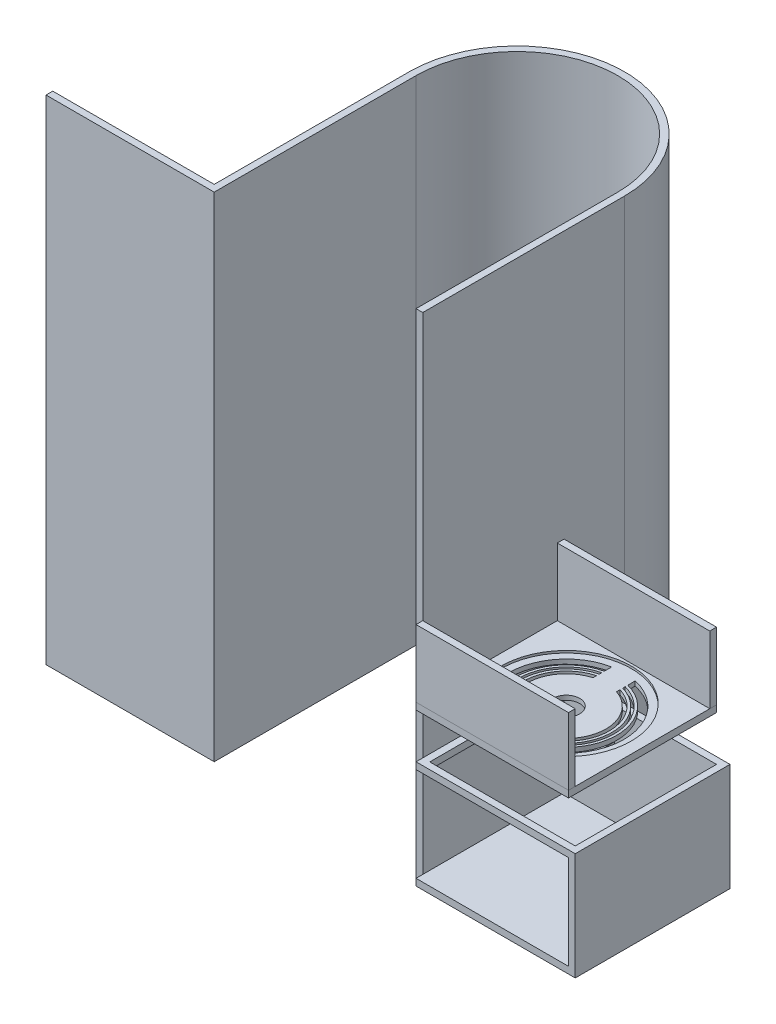
SolidWorks part; units mm, degrees
ref_plane "前视基准面" through (0, 0, 0) normal (0, 0, 1) x (1, 0, 0)
ref_plane "上视基准面" through (0, 0, 0) normal (0, 1, 0) x (1, 0, 0)
ref_plane "右视基准面" through (0, 0, 0) normal (1, 0, 0) x (0, 0, -1)
sketch "草图1" plane through (0, 0, 0) normal (0, 1, 0) x (1, 0, 0)
  line L0 (0, 0) -> (75, 0)
  line L1 (75, 0) -> (75, 90)
  line L3 (165, 0) -> (165, 90)
  arc A0 (75, 90) -> (165, 90) centre (120, 90) cw
extrude "拉伸-薄壁1" add sketch "草图1" along normal blind 220 thin thin type one direction wall 3
sketch "草图2" plane through (0, 0, 0) normal (0, 0, 1) x (1, 0, 0)
  line L0 (168, 220) -> (168, 0) construction
  line L2 (168, 71) -> (236, 71)
  point P7 (168, 71)
extrude "拉伸-薄壁2" add sketch "草图2" against normal blind 60 thin
ref_plane "基准面5" through (0, 71, 0) normal (0, 1, 0) x (1, 0, 0)
sketch "草图3" plane through (0, 71, 0) normal (0, 1, 0) x (1, 0, 0)
  circle A1 centre (202, 30) radius 6
  point P4 (202, 30)
  dimension "D1" = 12
extrude "切除-拉伸2" cut sketch "草图3" against normal blind 10
ref_plane "基准面6" through (0, 68, 0) normal (0, -1, 0) x (-1, 0, 0)
sketch "草图4" plane through (0, 68, 0) normal (0, -1, 0) x (-1, 0, 0)
  line L1 (-209.4957, 21.3148) -> (-194.5043, 21.3148)
  line L2 (-209.4957, 21.3148) -> (-209.4957, 16.0007)
  line L3 (-209.4957, 16.0007) -> (-194.5043, 16.0007)
  line L4 (-194.5043, 21.3148) -> (-194.5043, 16.0007)
  line L5 (-209.4957, 21.3148) -> (-194.5043, 16.0007) construction
  line L6 (-209.4957, 16.0007) -> (-194.5043, 21.3148) construction
  point P0 (-202, 18.6577)
extrude "凸台-拉伸2" add sketch "草图4" along normal blind 15
ref_plane "基准面9" through (0, 0, -16.0007) normal (0, 0, 1) x (1, 0, 0)
sketch "草图7" plane through (0, 0, -16.0007) normal (0, 0, 1) x (1, 0, 0)
  line L0 (194.5043, 53) -> (194.5043, 50)
  line L1 (194.5043, 50) -> (209.4957, 50)
  line L2 (209.4957, 50) -> (209.4957, 53)
  line L3 (209.4957, 53) -> (194.5043, 53)
extrude "凸台-拉伸3" add sketch "草图7" against normal blind 28
sketch "草图9" plane through (0, 71, 0) normal (0, 1, 0) x (1, 0, 0)
  circle A0 centre (202, 30) radius 29
  dimension "D1" = 58
extrude "切除-拉伸3" cut sketch "草图9" against normal blind 1
sketch "草图11" plane through (0, 71, 0) normal (0, 1, 0) x (1, 0, 0)
  circle A0 centre (202, 30) radius 25.7435
  circle A1 centre (202, 30) radius 29
ref_plane "基准面10" through (0, 0, 0) normal (0, 0, 1) x (1, 0, 0)
sketch "草图12" plane through (0, 0, 0) normal (0, 0, 1) x (1, 0, 0)
  line L0 (168, 71) -> (168, 68)
  line L1 (168, 68) -> (236, 68)
  line L2 (236, 68) -> (236, 71)
  line L3 (236, 71) -> (168, 71)
extrude "凸台-拉伸5" add sketch "草图12" along normal blind 3
sketch "草图13" plane through (0, 71, 0) normal (0, 1, 0) x (1, 0, 0)
  line L0 (167.9961, 0) -> (168, -3)
  line L1 (-1.65, 0) -> (1.65, 0) construction
  line L2 (168, -3) -> (236, -3)
  line L3 (236, -3) -> (236, 0)
  line L4 (236, 60) -> (236, -3) construction
  line L5 (236, 0) -> (167.9961, 0)
extrude "凸台-拉伸8" add sketch "草图13" along normal blind 30 separate body
ref_plane "基准面11" through (0, 0, -60) normal (0, 0, -1) x (-1, 0, 0)
sketch "草图15" plane through (0, 0, -60) normal (0, 0, -1) x (-1, 0, 0)
  line L0 (-236, 71) -> (-236, 68)
  line L1 (-236, 71) -> (-236, 68) construction
  line L2 (-236, 68) -> (-168, 68)
  line L3 (-168, 68) -> (-168, 71)
  line L4 (-168, 71) -> (-236, 71) construction
  line L5 (-168, 71) -> (-236, 71)
extrude "凸台-拉伸9" add sketch "草图15" along normal blind 3
sketch "草图16" plane through (0, 71, 0) normal (0, 1, 0) x (1, 0, 0)
  line L0 (168, 63) -> (168, 60)
  line L1 (168, 0) -> (168, 90) construction
  line L2 (168, 60) -> (236, 60)
  line L3 (236, 63) -> (236, -3) construction
  line L4 (236, 60) -> (236, 63)
  line L5 (236, 63) -> (168, 63)
extrude "凸台-拉伸10" add sketch "草图16" along normal blind 30 separate body
sketch "草图17" plane through (0, 71, 0) normal (0, 1, 0) x (1, 0, 0)
  line L1 (197.0036, 55.254) -> (197.0036, 51.9491)
  line L2 (207.6323, 55.1198) -> (207.6323, 51.7946)
  line L3 (197.0036, 49.7009) -> (197.0036, 50.8201)
  line L4 (197.0036, 46.9436) -> (197.0036, 48.518)
  line L5 (207.6323, 50.6571) -> (207.6323, 49.5287)
  line L6 (207.6323, 46.743) -> (207.6323, 48.3346)
  arc A0 (197.0036, 55.254) -> (207.6323, 55.1198) centre (202, 30) ccw
  arc A1 (197.0036, 51.9491) -> (207.6323, 51.7946) centre (202, 30) ccw
  arc A2 (197.0036, 48.518) -> (207.6323, 48.3346) centre (202, 30) ccw
  arc A3 (197.0036, 50.8201) -> (207.6323, 50.6571) centre (202, 30) ccw
  circle A4 centre (202, 30) radius 4.9964
  arc A5 (197.0036, 49.7009) -> (207.6323, 49.5287) centre (202, 30) ccw
  arc A6 (197.0036, 46.9436) -> (207.6323, 46.743) centre (202, 30) ccw
extrude "切除-拉伸6" cut sketch "草图17" against normal blind 30
sketch "草图24" plane through (0, 0, 0) normal (0, 1, 0) x (1, 0, 0)
  line L0 (168, 0) -> (168, 90) construction
  line L1 (236, -3) -> (168, -3)
  line L2 (236, -3) -> (236, 63)
  line L3 (236, 63) -> (168, 63)
  line L4 (168, -3) -> (168, 63)
  line L5 (236, -3) -> (168, 63) construction
  line L6 (236, 63) -> (168, -3) construction
  line L7 (168, 63) -> (168, 60) construction
  point P0 (202, 30)
extrude "凸台-拉伸14" add sketch "草图24" along normal blind 3
sketch "草图25" plane through (0, 0, 0) normal (0, 1, 0) x (1, 0, 0)
  line L0 (168, 63) -> (168, 66)
  line L1 (168, 0) -> (168, 90) construction
  line L2 (168, 66) -> (236, 66)
  line L3 (236, 66) -> (239, 66)
  line L4 (239, 66) -> (239, -3)
  line L5 (239, -3) -> (236, -3)
  line L6 (236, -3) -> (236, 63)
  line L7 (236, 63) -> (168, 63)
extrude "凸台-拉伸15" add sketch "草图25" along normal blind 45
ref_plane "基准面17" through (0, 45, 0) normal (0, 1, 0) x (1, 0, 0)
sketch "草图28" plane through (0, 45, 0) normal (0, 1, 0) x (1, 0, 0)
  line L0 (168, 66) -> (239, 66)
  line L1 (239, 66) -> (239, -3)
  line L2 (239, -3) -> (168, -3)
  line L3 (168, -3) -> (168, 66)
  line L4 (171.1074, 63) -> (171.1074, 0)
  line L5 (168, 63) -> (236, 63) construction
  line L6 (171.1074, 0) -> (236, 0)
  line L7 (236, 0) -> (236, 63)
  line L8 (236, 63) -> (171.1074, 63)
extrude "凸台-拉伸16" add sketch "草图28" along normal blind 3
